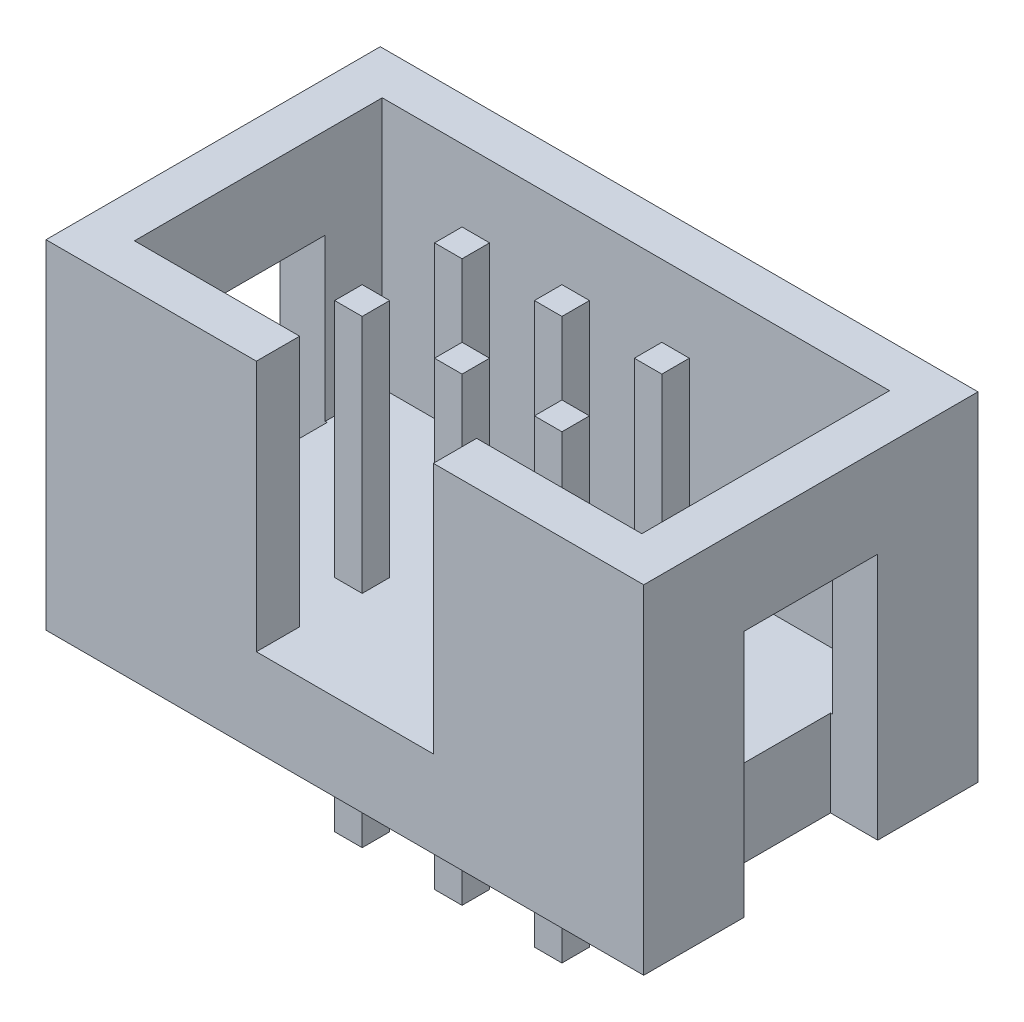
SolidWorks part; units mm, degrees
ref_plane "Front Plane" through (0, 0, 0) normal (0, 0, 1) x (1, 0, 0)
ref_plane "Top Plane" through (0, 0, 0) normal (0, 1, 0) x (1, 0, 0)
ref_plane "Right Plane" through (0, 0, 0) normal (1, 0, 0) x (0, 0, -1)
sketch "Sketch1" plane through (0, 0, 0) normal (0, 1, 0) x (1, 0, 0)
  line L1 (-7.6, -4.25) -> (7.6, -4.25)
  line L2 (-7.6, -4.25) -> (-7.6, 4.25)
  line L3 (-7.6, 4.25) -> (7.6, 4.25)
  line L4 (7.6, -4.25) -> (7.6, 4.25)
  line L5 (-7.6, -4.25) -> (7.6, 4.25) construction
  line L6 (-7.6, 4.25) -> (7.6, -4.25) construction
  point P0 (0, 0)
  dimension "D1" = 8.5
  dimension "D2" = 15.2
extrude "Boss-Extrude1" add sketch "Sketch1" along normal blind 8.6
sketch "Sketch2" plane through (0, 8.6, 0) normal (0, 1, 0) x (1, 0, 0)
  line L1 (-6.45, -3.15) -> (6.45, -3.15)
  line L2 (-6.45, -3.15) -> (-6.45, 3.15)
  line L3 (-6.45, 3.15) -> (6.45, 3.15)
  line L4 (6.45, -3.15) -> (6.45, 3.15)
  line L5 (-6.45, -3.15) -> (6.45, 3.15) construction
  line L6 (-6.45, 3.15) -> (6.45, -3.15) construction
  point P0 (0, 0)
  dimension "D1" = 6.3
  dimension "D2" = 12.9
extrude "Cut-Extrude1" cut sketch "Sketch2" against normal blind 6.4
sketch "Sketch3" plane through (0, 8.6, 0) normal (0, 1, 0) x (1, 0, 0)
  line L0 (-6.45, -3.15) -> (6.45, -3.15) construction
  line L1 (-2.25, -3.15) -> (2.25, -3.15)
  line L2 (-2.25, -3.15) -> (-2.25, -4.25)
  line L3 (-2.25, -4.25) -> (2.25, -4.25)
  line L4 (2.25, -3.15) -> (2.25, -4.25)
  line L5 (-7.6, -4.25) -> (7.6, -4.25) construction
  line L6 (0, -4.25) -> (0, 0) construction
  dimension "D1" = 4.5
extrude "Cut-Extrude2" cut sketch "Sketch3" against normal up to surface (6.4 mm away) up to face at (0, 2.2, 0)
sketch "Sketch4" plane through (0, 0, 0) normal (0, -1, 0) x (1, 0, 0)
  line L0 (7.6, 4.25) -> (7.6, -4.25) construction
  line L1 (7.6, -1.7) -> (6.4, -1.7)
  line L2 (7.6, -1.7) -> (7.6, 1.7)
  line L3 (7.6, 1.7) -> (6.4, 1.7)
  line L4 (6.4, -1.7) -> (6.4, 1.7)
  line L5 (7.6, 0) -> (0, 0) construction
  dimension "D1" = 3.4
  dimension "D2" = 1.2
extrude "Cut-Extrude3" cut sketch "Sketch4" against normal blind 6.3
sketch "Sketch6" plane through (0, 0, 0) normal (0, -1, 0) x (1, 0, 0)
  line L0 (7.6, -4.25) -> (-7.6, -4.25) construction
  line L1 (4.5, -4.25) -> (5.4, -4.25)
  line L2 (4.5, -4.25) -> (4.5, -4.55)
  line L3 (4.5, -4.55) -> (5.4, -4.55)
  line L4 (5.4, -4.25) -> (5.4, -4.55)
  dimension "D1" = 0.3
  dimension "D2" = 0.9
  dimension "D3" = 4.5
extrude "Boss-Extrude2" add sketch "Sketch6" against normal blind 7.8
mirror "Mirror1" about plane through (0, 0, 0) normal (1, 0, 0) of "Boss-Extrude2", "Cut-Extrude3"
sketch "Sketch7" plane through (0, 0, 0) normal (0, -1, 0) x (1, 0, 0)
  line L1 (-2.89, -1.62) -> (-2.19, -1.62)
  line L2 (-2.89, -1.62) -> (-2.89, -0.92)
  line L3 (-2.89, -0.92) -> (-2.19, -0.92)
  line L4 (-2.19, -1.62) -> (-2.19, -0.92)
  line L5 (-2.89, -1.62) -> (-2.19, -0.92) construction
  line L6 (-2.89, -0.92) -> (-2.19, -1.62) construction
  point P0 (-2.54, -1.27)
  point P8 (-2.54, -2.569)
  dimension "D1" = 0.7
  dimension "D2" = 2.54
  dimension "D3" = 1.27
extrude "Boss-Extrude3" add sketch "Sketch7" along normal blind 3.4 and the other way blind 8.3
pattern_linear "LPattern1" count 3 spacing 2.54 along (1, 0, 0) count 2 spacing 2.54 along (0, 0, 1) of "Boss-Extrude3"
